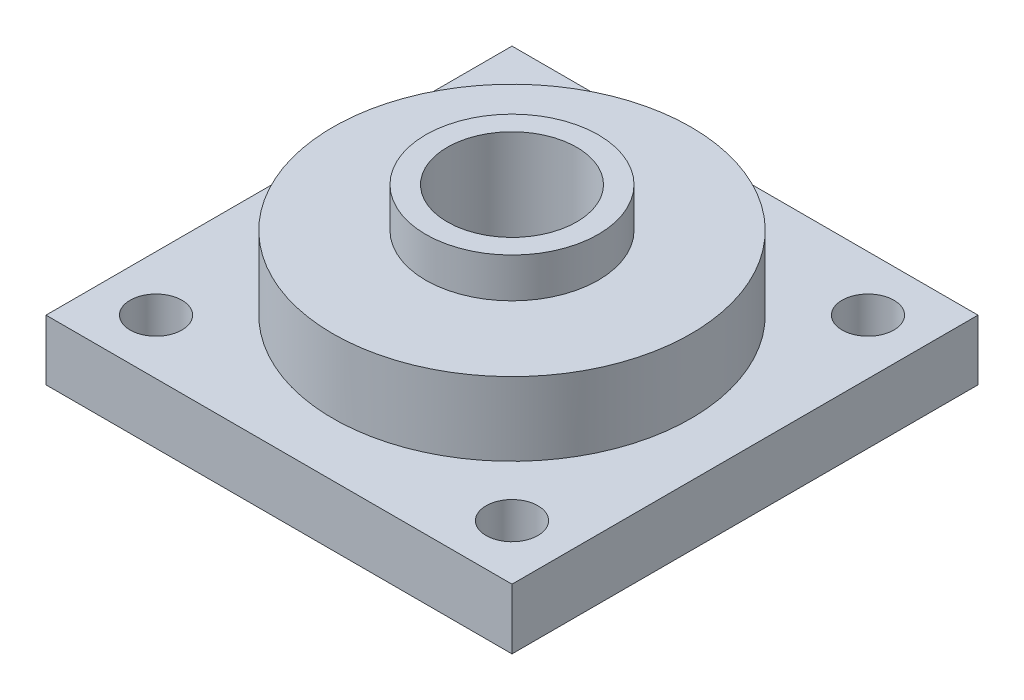
SolidWorks part; units mm, degrees
ref_plane "Front Plane" through (0, 0, 0) normal (0, 0, 1) x (1, 0, 0)
ref_plane "Top Plane" through (0, 0, 0) normal (0, 1, 0) x (1, 0, 0)
ref_plane "Right Plane" through (0, 0, 0) normal (1, 0, 0) x (0, 0, -1)
sketch "Sketch1" plane through (0, 0, 0) normal (0, 1, 0) x (1, 0, 0)
  line L1 (0, 0) -> (108, 0)
  line L2 (0, 0) -> (0, 108)
  line L3 (0, 108) -> (108, 108)
  line L4 (108, 0) -> (108, 108)
  circle A0 centre (12.75, 12.75) radius 6
  circle A4 centre (54, 54) radius 15
  circle A5 centre (95.25, 12.75) radius 6
  circle A6 centre (95.25, 95.25) radius 6
  circle A7 centre (12.75, 95.25) radius 6
  dimension "D3" = 30
  dimension "D8" = 12
  dimension "D11" = 82.5
  dimension "D1" = 108
  dimension "D2" = 108
  dimension "D4" = 12.75
  dimension "D5" = 12.75
  dimension "D6" = 54
  dimension "D7" = 54
  dimension "D12" = 82.5
  dimension "D9" = 2
  dimension "D10" = 2
extrude "Boss-Extrude1" add sketch "Sketch1" along normal blind 14
sketch "Sketch2" plane through (0, 14, 0) normal (0, 1, 0) x (1, 0, 0)
  circle A0 centre (54, 54) radius 20
  circle A1 centre (54, 54) radius 15
  dimension "D1" = 30
  dimension "D2" = 40
extrude "Boss-Extrude2" add sketch "Sketch2" along normal blind 26.2
sketch "Sketch3" plane through (0, 14, 0) normal (0, 1, 0) x (1, 0, 0)
  circle A0 centre (54, 54) radius 41.5
  circle A1 centre (54, 54) radius 15
  dimension "D1" = 83
  dimension "D2" = 30
extrude "Boss-Extrude3" add sketch "Sketch3" along normal blind 17
